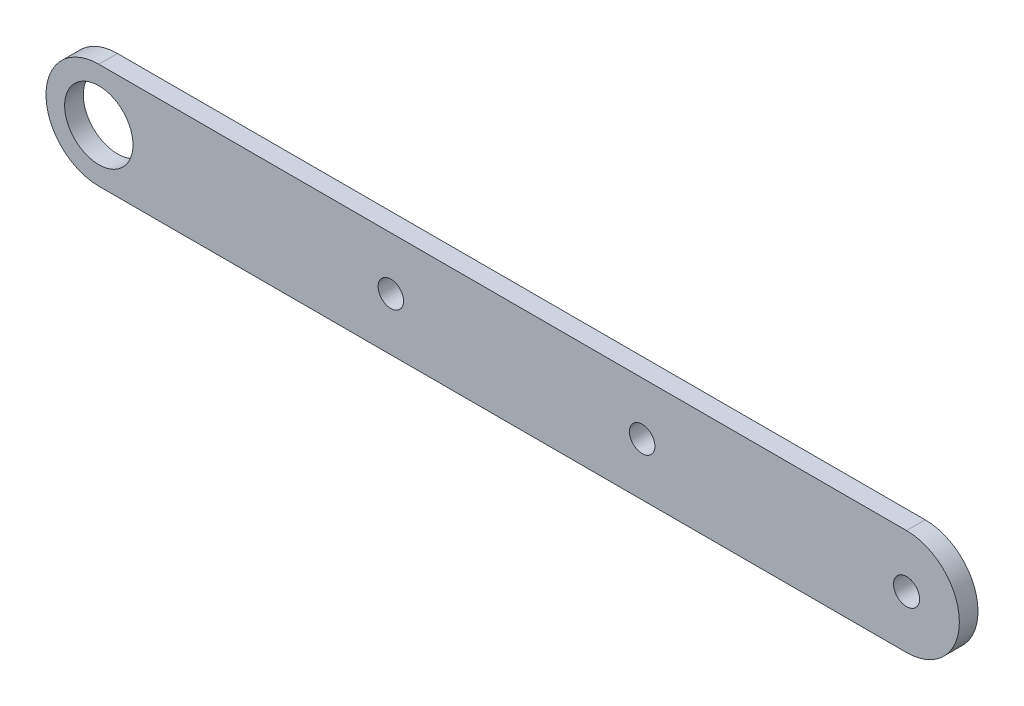
SolidWorks part; units mm, degrees
ref_plane "Plan de face" through (0, 0, 0) normal (0, 0, 1) x (1, 0, 0)
ref_plane "Plan de dessus" through (0, 0, 0) normal (0, 1, 0) x (1, 0, 0)
ref_plane "Plan de droite" through (0, 0, 0) normal (1, 0, 0) x (0, 0, -1)
sketch "Esquisse1" plane through (0, 0, 0) normal (0, 0, 1) x (1, 0, 0)
  line L0 (-130, 0) -> (0, 0) construction
  line L1 (-130, 8.5) -> (0, 8.5)
  line L2 (-130, -8.5) -> (0, -8.5)
  line L3 (-83, 2.05) -> (-42.55, 2.05) construction
  circle A0 centre (0, 0) radius 2.1
  circle A1 centre (-130, 0) radius 5.5
  arc A2 (-130, 8.5) -> (-130, -8.5) centre (-130, 0) ccw
  arc A3 (0, -8.5) -> (0, 8.5) centre (0, 0) ccw
  circle A4 centre (-83, 0) radius 2.05
  circle A5 centre (-42.55, 0) radius 2.05
  circle A6 centre (-42.55, 0) radius 2.05 construction
  point P5 (-65, 0)
  point P10 (-130, 5.5)
  dimension "D1" = 11
  dimension "D4" = 4.1
  dimension "D5" = 4.2
  dimension "D2" = 130
  dimension "D3" = 3
  dimension "D6" = 40.45
  dimension "D7" = 42.55
extrude "Boss.-Extru.1" add sketch "Esquisse1" along normal blind 3
